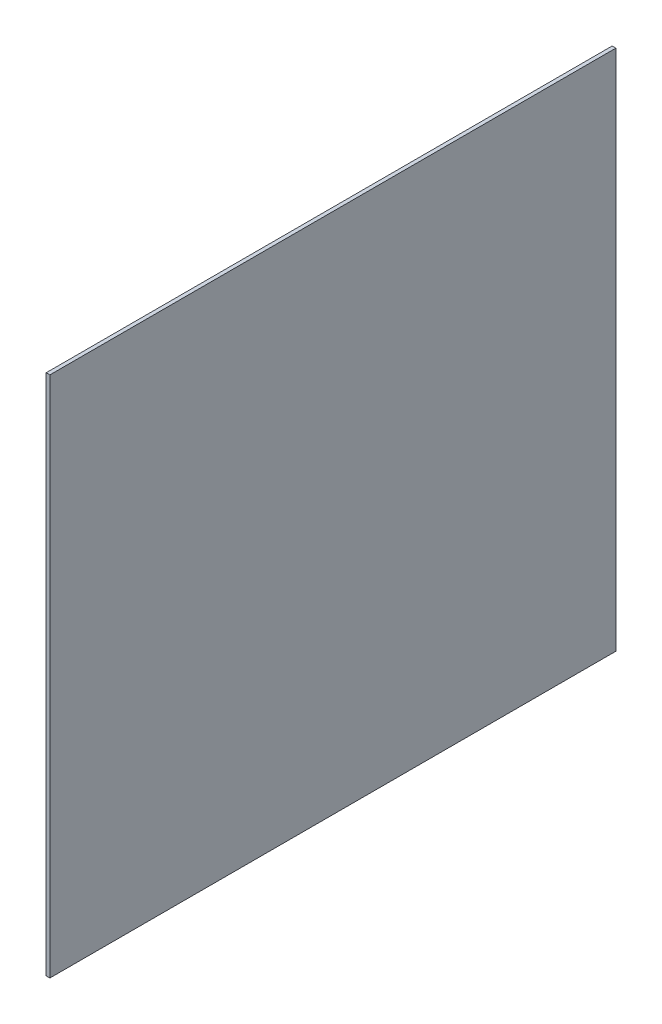
SolidWorks part; units mm, degrees
ref_plane "Front Plane" through (0, 0, 0) normal (0, 0, 1) x (1, 0, 0)
ref_plane "Top Plane" through (0, 0, 0) normal (0, 1, 0) x (1, 0, 0)
ref_plane "Right Plane" through (0, 0, 0) normal (1, 0, 0) x (0, 0, -1)
sketch "Sketch1" plane through (0, 0, 0) normal (1, 0, 0) x (0, 0, -1)
  line L1 (-228.6, 211) -> (228.6, 211)
  line L2 (-228.6, 211) -> (-228.6, -211)
  line L3 (-228.6, -211) -> (228.6, -211)
  line L4 (228.6, 211) -> (228.6, -211)
  line L5 (-228.6, 211) -> (228.6, -211) construction
  line L6 (-228.6, -211) -> (228.6, 211) construction
  point P0 (0, 0)
  dimension "D1" = 457.2
  dimension "D2" = 422
extrude "Boss-Extrude1" add sketch "Sketch1" along normal blind 3
